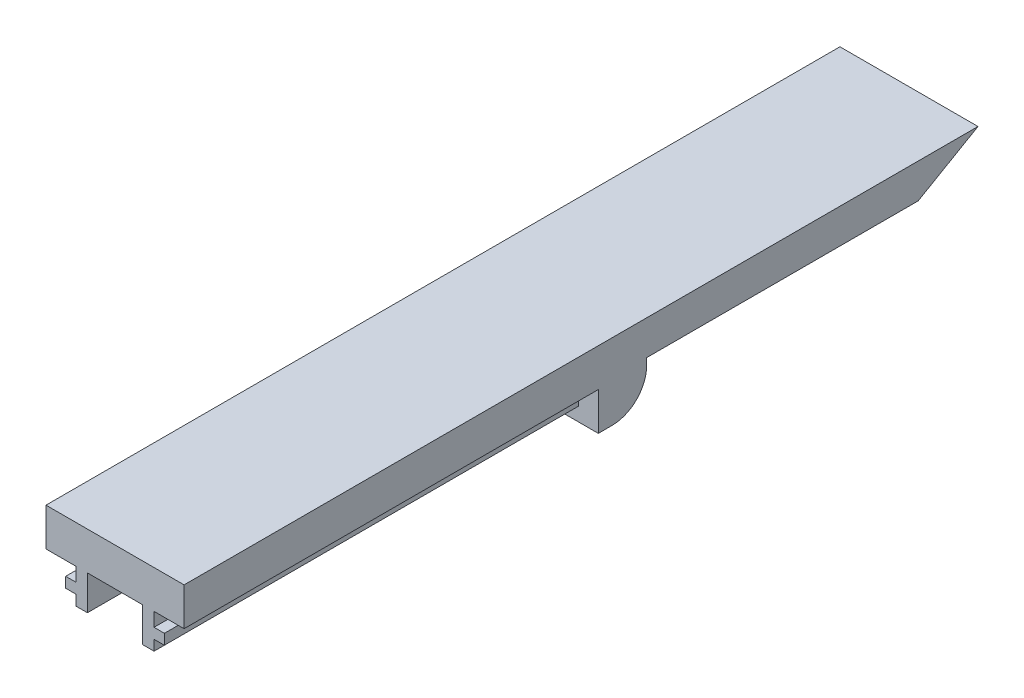
SolidWorks part; units mm, degrees
ref_plane "Front Plane" through (0, 0, 0) normal (0, 0, 1) x (1, 0, 0)
ref_plane "Top Plane" through (0, 0, 0) normal (0, 1, 0) x (1, 0, 0)
ref_plane "Right Plane" through (0, 0, 0) normal (1, 0, 0) x (0, 0, -1)
sketch "Sketch1" plane through (0, 0, 0) normal (0, 0, 1) x (1, 0, 0)
  line L1 (-26.5363, 10.2235) -> (-6.5363, 10.2235)
  line L2 (-26.5363, 10.2235) -> (-26.5363, 2.2235)
  line L3 (-26.5363, 2.2235) -> (-6.5363, 2.2235)
  line L4 (-6.5363, 10.2235) -> (-6.5363, 2.2235)
  dimension "D1" = 20
  dimension "D2" = 8
extrude "Boss-Extrude1" add sketch "Sketch1" against normal blind 115
sketch "Sketch2" plane through (0, 0, 0) normal (0, 0, 1) x (1, 0, 0)
  line L0 (-26.5363, 10.2235) -> (-26.5363, 2.2235) construction
  line L1 (-26.5363, 7.7235) -> (-22.1863, 7.7235)
  line L2 (-22.1863, 7.7235) -> (-22.1863, 5.7235)
  line L3 (-22.1863, 5.7235) -> (-23.6863, 5.7235)
  line L4 (-23.6863, 5.7235) -> (-23.6863, 4.2235)
  line L5 (-23.6863, 4.2235) -> (-22.1863, 4.2235)
  line L6 (-22.1863, 4.2235) -> (-22.1863, 2.7235)
  line L7 (-22.1863, 2.7235) -> (-20.5363, 2.7235)
  line L8 (-20.5363, 2.7235) -> (-20.5363, 7.7235)
  line L9 (-20.5363, 7.7235) -> (-12.5363, 7.7235)
  line L10 (-16.5363, 10.2235) -> (-16.5363, 5.2831) construction
  line L11 (-6.5363, 10.2235) -> (-26.5363, 10.2235) construction
  line L13 (-26.5363, 7.7235) -> (-26.5363, 2.2235)
  line L15 (-12.5363, 2.7235) -> (-12.5363, 7.7235)
  line L16 (-10.8863, 2.7235) -> (-12.5363, 2.7235)
  line L17 (-10.8863, 4.2235) -> (-10.8863, 2.7235)
  line L18 (-9.3863, 4.2235) -> (-10.8863, 4.2235)
  line L19 (-9.3863, 5.7235) -> (-9.3863, 4.2235)
  line L20 (-10.8863, 5.7235) -> (-9.3863, 5.7235)
  line L21 (-10.8863, 7.7235) -> (-10.8863, 5.7235)
  line L22 (-6.5363, 7.7235) -> (-10.8863, 7.7235)
  line L23 (-6.5363, 7.7235) -> (-6.5363, 2.2235)
  line L24 (-26.5363, 2.2235) -> (-6.5363, 2.2235)
  point P23 (-16.5363, 7.7235)
  dimension "D2" = 2.5
  dimension "D3" = 4.35
  dimension "D4" = 2
  dimension "D5" = 1.5
  dimension "D6" = 1.5
  dimension "D7" = 1.5
  dimension "D8" = 1.65
extrude "Cut-Extrude1" cut sketch "Sketch2" against normal blind 60
sketch "Sketch3" plane through (0, 10.2235, 0) normal (0, 1, 0) x (1, 0, 0)
  line L4 (-26.5363, 0) -> (-6.5363, 0)
  line L5 (-6.5363, 0) -> (-6.5363, 115)
  line L6 (-6.5363, 115) -> (-26.5363, 115)
  line L7 (-26.5363, 115) -> (-26.5363, 0)
  line L8 (-26.5363, 0) -> (-6.5363, 0)
  line L9 (-6.5363, 0) -> (-6.5363, 115)
  line L10 (-6.5363, 115) -> (-26.5363, 115)
  line L11 (-26.5363, 115) -> (-26.5363, 0)
  dimension "D1" = 0
extrude "Boss-Extrude2" add sketch "Sketch3" along normal blind 3
ref_plane "Plane1" through (0, -39.8789, -23.0241) normal (0, 0.866, 0.5) x (-1, 0, 0)
sketch "Sketch13" plane through (0, -39.8789, -23.0241) normal (0, 0.866, 0.5) x (-1, 0, 0)
  line L5 (39.5856, -68.4) -> (-7.1505, -68.4)
  line L6 (39.5856, -68.4) -> (39.5856, -132.2421)
  line L7 (39.5856, -132.2421) -> (-7.1505, -132.2421)
  line L8 (-7.1505, -68.4) -> (-7.1505, -132.2421)
extrude "Cut-Extrude5" cut sketch "Sketch13" against normal blind 30
sketch "Sketch15" plane through (0, 2.2235, 0) normal (0, -1, 0) x (1, 0, 0)
  line L14 (-26.5363, -95.9474) -> (-26.5363, -60) construction
  line L15 (-26.5363, -67) -> (-6.5363, -67)
  line L16 (-26.5363, -67) -> (-26.5363, -107)
  line L17 (-26.5363, -107) -> (-6.5363, -107)
  line L18 (-6.5363, -67) -> (-6.5363, -107)
  line L19 (-6.5363, -95.9474) -> (-6.5363, -60) construction
  line L20 (-26.5363, -60) -> (-6.5363, -60) construction
  dimension "D1" = 7
  dimension "D2" = 40
extrude "Cut-Extrude6" cut sketch "Sketch15" against normal blind 6
fillet "Fillet1" radius 5 1 edges at (-16.5363, 2.2235, -67)
